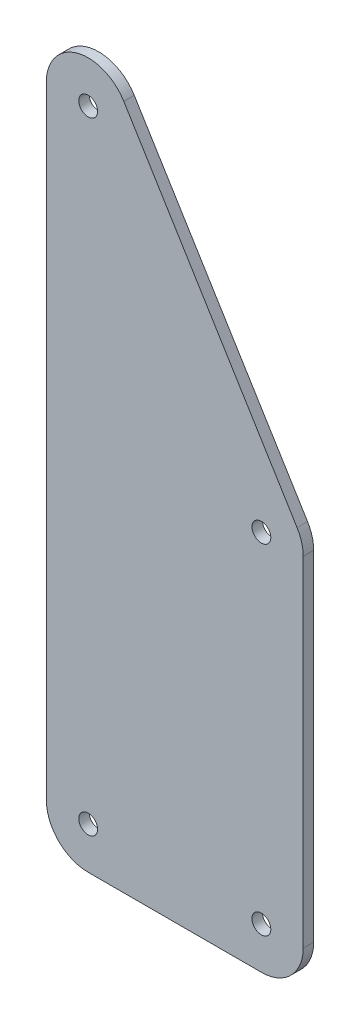
SolidWorks part; units mm, degrees
ref_plane "前视基准面" through (0, 0, 0) normal (0, 0, 1) x (1, 0, 0)
ref_plane "上视基准面" through (0, 0, 0) normal (0, 1, 0) x (1, 0, 0)
ref_plane "右视基准面" through (0, 0, 0) normal (1, 0, 0) x (0, 0, -1)
sketch "草图1" plane through (0, 0, 0) normal (0, 0, 1) x (1, 0, 0)
  line L0 (40, 0) -> (205.6, 0)
  line L1 (245.6, 40) -> (245.6, 364.3604)
  line L2 (0, 40) -> (0, 634.3571)
  line L3 (74.0974, 655.2705) -> (239.6974, 385.2737)
  arc A0 (0, 634.3571) -> (74.0974, 655.2705) centre (40, 634.3571) cw
  arc A1 (245.6, 364.3604) -> (239.6974, 385.2737) centre (205.6, 364.3604) ccw
  arc A2 (205.6, 0) -> (245.6, 40) centre (205.6, 40) ccw
  arc A3 (40, 0) -> (0, 40) centre (40, 40) cw
  point P7 (0, 776.08)
  point P10 (245.6, 375.65)
  point P13 (245.6, 0)
  point P16 (0, 0)
  dimension "D4" = 40
  dimension "D5" = 40
  dimension "D1" = 245.6
  dimension "D2" = 375.65
  dimension "D3" = 776.08
extrude "凸台-拉伸1" add sketch "草图1" along normal blind 10
sketch "草图2" plane through (0, 0, 0) normal (0, 0, -1) x (-1, 0, 0)
  line L8 (-40, 634.3571) -> (-205.6, 364.3604)
  line L9 (-205.6, 364.3604) -> (-205.6, 40)
  line L10 (-205.6, 40) -> (-40, 40)
  line L11 (-40, 40) -> (-40, 634.3571)
  line L12 (-40, 634.3571) -> (-205.6, 364.3604) construction
  line L13 (-205.6, 364.3604) -> (-205.6, 40) construction
  line L14 (-205.6, 40) -> (-40, 40) construction
  line L15 (-40, 40) -> (-40, 634.3571) construction
  circle A4 centre (-40, 634.3571) radius 9
  circle A5 centre (-205.6, 364.3604) radius 9
  circle A6 centre (-40, 40) radius 9
  circle A7 centre (-205.6, 40) radius 9
  dimension "D2" = 18
  dimension "D3" = 18
  dimension "D4" = 18
  dimension "D5" = 18
  dimension "D1" = 40
extrude "切除-拉伸1" cut sketch "草图2" against normal blind 20
scale "缩放比例1" scale about origin uniform scaling yes scale factor 0.8
